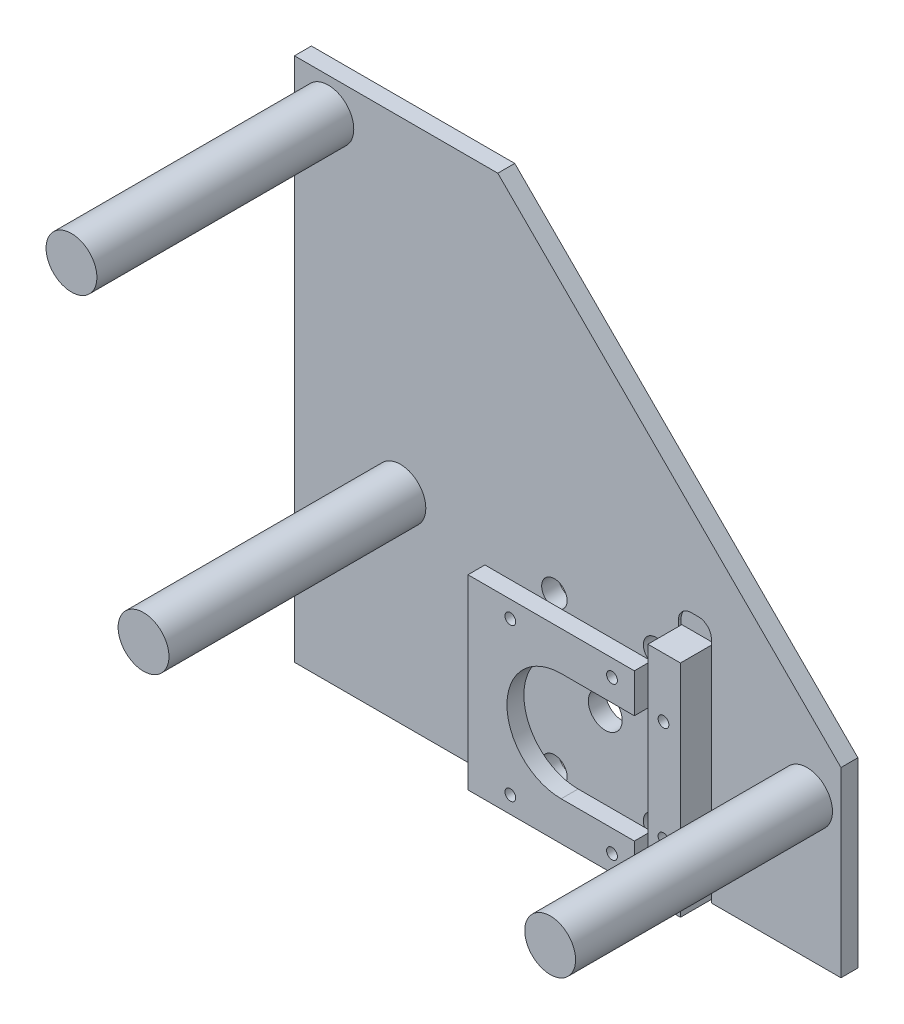
SolidWorks part; units mm, degrees
material "ASTM A36 Steel"
ref_plane "Front Plane" through (0, 0, 0) normal (0, 0, 1) x (1, 0, 0)
ref_plane "Top Plane" through (0, 0, 0) normal (0, 1, 0) x (1, 0, 0)
ref_plane "Right Plane" through (0, 0, 0) normal (1, 0, 0) x (0, 0, -1)
sketch "Sketch1" plane through (0, 0, 0) normal (0, 0, 1) x (1, 0, 0)
  line L4 (-131.7752, 23.8252) -> (-131.7752, -173.0248)
  line L5 (-131.7752, -173.0248) -> (73.025, -173.0248)
  line L6 (73.025, -173.0248) -> (73.025, -104.775)
  line L7 (73.025, -104.775) -> (-55.5752, 23.8252)
  line L8 (-55.5752, 23.8252) -> (-131.7752, 23.8252)
  circle A0 centre (-92.075, -98.425) radius 2.4257
  circle A1 centre (-119.0752, 11.1252) radius 2.4257
  circle A2 centre (60.325, -120.65) radius 2.4257
  dimension "D1" = 119.0752
  dimension "D4" = 92.075
  dimension "D5" = 98.425
  dimension "D8" = 60.325
  dimension "D10" = 4.8514
  dimension "D15" = 12.7
  dimension "D16" = 12.7
  dimension "D2" = 12.7
  dimension "D9" = 120.65
  dimension "D11" = 11.1252
  dimension "D13" = 45
  dimension "D17" = 76.2
  dimension "D18" = 196.85
extrude "Boss-Extrude1" add sketch "Sketch1" against normal blind 6.35
sketch "Sketch4" plane through (0, 0, 0) normal (0, 0, 1) x (1, 0, 0)
  circle A0 centre (-15.3162, -130.5052) radius 6.35
  circle A1 centre (3.7338, -101.9302) radius 4.7625
  circle A2 centre (-34.3662, -101.9302) radius 4.7625
  circle A3 centre (-34.3662, -159.0802) radius 4.7625
  circle A4 centre (3.7338, -159.0802) radius 4.7625
  circle A5 centre (18.2118, -111.4552) radius 2.4257
  circle A6 centre (18.2118, -149.5552) radius 2.4257
  dimension "D1" = 9.525
  dimension "D2" = 12.7
  dimension "D3" = 19.05
  dimension "D4" = 19.05
  dimension "D5" = 28.575
  dimension "D6" = 130.5052
  dimension "D7" = 15.3162
  dimension "D8" = 28.575
  dimension "D9" = 19.05
  dimension "D10" = 19.05
  dimension "D11" = 33.528
  dimension "D12" = 4.8514
extrude "Cut-Extrude1" cut sketch "Sketch4" against normal blind 12.7
sketch "Sketch6" plane through (0, 0, 0) normal (0, 0, 1) x (1, 0, 0)
  line L0 (12.1158, -87.3252) -> (12.1158, -179.3748)
  line L1 (16.891, -184.15) -> (19.685, -184.15)
  line L2 (24.4602, -179.3748) -> (24.4602, -87.3252)
  line L3 (19.685, -82.55) -> (16.891, -82.55)
  arc A0 (12.1158, -179.3748) -> (16.891, -184.15) centre (16.891, -179.3748) ccw
  arc A1 (12.1158, -87.3252) -> (16.891, -82.55) centre (16.891, -87.3252) cw
  arc A2 (24.4602, -87.3252) -> (19.685, -82.55) centre (19.685, -87.3252) ccw
  arc A3 (19.685, -184.15) -> (24.4602, -179.3748) centre (19.685, -179.3748) ccw
  dimension "D1" = 4.7752
  dimension "D2" = 12.3444
  dimension "D3" = 101.6
  dimension "D4" = 27.432
  dimension "D5" = 82.55
extrude "Cut-Extrude2" cut sketch "Sketch6" against normal blind 1.016
sketch "Sketch2" plane through (0, 0, 0) normal (0, 0, 1) x (1, 0, 0)
  circle A0 centre (-119.0752, 11.1252) radius 9.525
  circle A1 centre (-92.075, -98.425) radius 9.525
  circle A2 centre (60.325, -120.65) radius 9.525
  dimension "D1" = 19.05
extrude "Boss-Extrude2" add sketch "Sketch2" along normal blind 96.266 separate body
sketch "Sketch3" plane through (0, 0, -1.016) normal (0, 0, 1) x (1, 0, 0)
  line L1 (12.3698, -89.2302) -> (24.5618, -89.2302)
  line L2 (12.3698, -89.2302) -> (12.3698, -171.7802)
  line L3 (12.3698, -171.7802) -> (24.5618, -171.7802)
  line L4 (24.5618, -89.2302) -> (24.5618, -171.7802)
  circle A0 centre (-15.3162, -130.5052) radius 6.35 construction
  circle A1 centre (18.2118, -111.4552) radius 2.0193
  circle A2 centre (18.2118, -149.5552) radius 2.0193
  point P7 (12.3698, -130.5052)
  dimension "D5" = 27.686
  dimension "D6" = 4.0386
  dimension "D1" = 12.3698
  dimension "D2" = 12.192
  dimension "D3" = 89.2302
  dimension "D4" = 82.55
extrude "Boss-Extrude3" add sketch "Sketch3" along normal blind 12.7 separate body
ref_plane "Plane1" through (0, 0, 10.16) normal (0, 0, 1) x (1, 0, 0)
sketch "Sketch5" plane through (0, 0, 10.16) normal (0, 0, 1) x (1, 0, 0)
  line L0 (12.1158, -95.5802) -> (-50.2412, -95.5802)
  line L1 (-50.2412, -95.5802) -> (-50.2412, -165.4302)
  line L2 (-50.2412, -165.4302) -> (12.1158, -165.4302)
  line L3 (12.1158, -165.4302) -> (12.1158, -150.8252)
  line L4 (12.1158, -150.8252) -> (-15.3162, -150.8252)
  line L5 (-15.3162, -110.1852) -> (12.1158, -110.1852)
  line L6 (12.1158, -110.1852) -> (12.1158, -95.5802)
  arc A0 (-15.3162, -150.8252) -> (-15.3162, -110.1852) centre (-15.3162, -130.5052) cw
  circle A1 centre (3.7338, -101.9302) radius 2.0193
  circle A2 centre (-34.3662, -101.9302) radius 2.0193
  circle A3 centre (-34.3662, -159.0802) radius 2.0193
  circle A4 centre (3.7338, -159.0802) radius 2.0193
  dimension "D1" = 20.32
  dimension "D2" = 34.925
  dimension "D6" = 4.0386
  dimension "D3" = 34.925
  dimension "D4" = 34.925
  dimension "D5" = 27.432
extrude "Boss-Extrude4" add sketch "Sketch5" along normal blind 6.35 separate body
